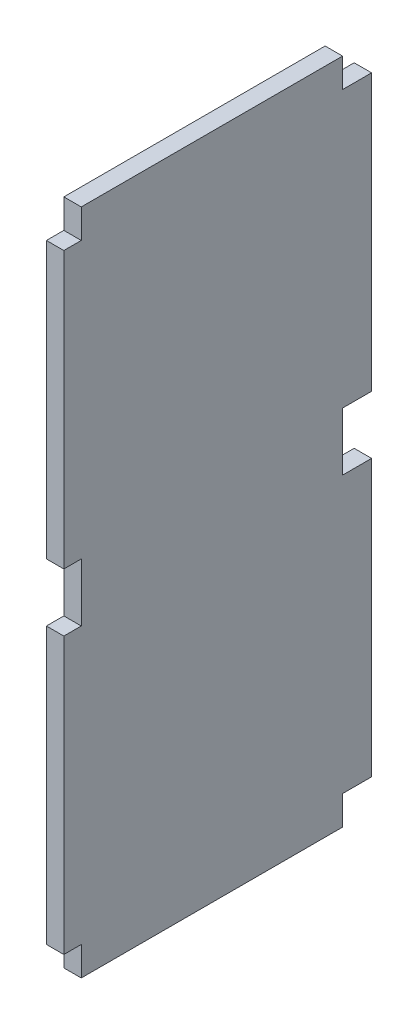
SolidWorks part; units mm, degrees
material "PVC rigido"
ref_plane "Piano frontale" through (0, 0, 0) normal (0, 0, 1) x (1, 0, 0)
ref_plane "Piano superiore" through (0, 0, 0) normal (0, 1, 0) x (1, 0, 0)
ref_plane "Piano destro" through (0, 0, 0) normal (1, 0, 0) x (0, 0, -1)
sketch "Schizzo1" plane through (0, 0, 0) normal (0, 0, 1) x (1, 0, 0)
  line L1 (6.5, 52.5) -> (3.5, 52.5)
  line L2 (6.5, 52.5) -> (6.5, -52.5)
  line L3 (6.5, -52.5) -> (3.5, -52.5)
  line L4 (3.5, 52.5) -> (3.5, -52.5)
extrude "Estrusione-Estrusione1" add sketch "Schizzo1" along normal up to surface (48 mm away) and the other way up to surface (5 mm away)
ref_plane "Piano1" through (0, 0, 0) normal (0, -1, 0) x (-1, 0, 0)
sketch "Schizzo2" plane through (6.5, 0, 0) normal (1, 0, 0) x (0, 0, -1)
  line L0 (-48, -52.5) -> (-48, 52.5) construction
  line L1 (-48, -5) -> (-45, -5)
  line L2 (-48, -5) -> (-48, 5)
  line L3 (-48, 5) -> (-45, 5)
  line L4 (-45, 5) -> (-45, 0)
  line L5 (5, -52.5) -> (5, 52.5) construction
  line L6 (5, -5) -> (0, -5)
  line L7 (5, -5) -> (5, 5)
  line L8 (5, 5) -> (0, 5)
  line L9 (0, 5) -> (0, 0)
  line L11 (-45, 0) -> (-45, -5)
  line L12 (-1.65, 0) -> (1.65, 0) construction
  line L13 (0, 0) -> (0, -5)
  line L14 (-45, -5) -> (-48, -5) construction
extrude "Taglio-Estrusione1" cut sketch "Schizzo2" against normal blind 10
sketch "Schizzo3" plane through (0, -52.5, 0) normal (0, -1, 0) x (1, 0, 0)
  line L0 (6.5, 48) -> (6.5, -5) construction
  line L1 (3.5, 0) -> (6.5, 0)
  line L2 (3.5, 0) -> (3.5, 45)
  line L3 (3.5, 45) -> (6.5, 45)
  line L4 (6.5, 0) -> (6.5, 45)
extrude "Estrusione-Estrusione2" add sketch "Schizzo3" along normal blind 5
mirror "Specchia1" about plane through (0, 0, 0) normal (0, -1, 0) of "Estrusione-Estrusione2"
